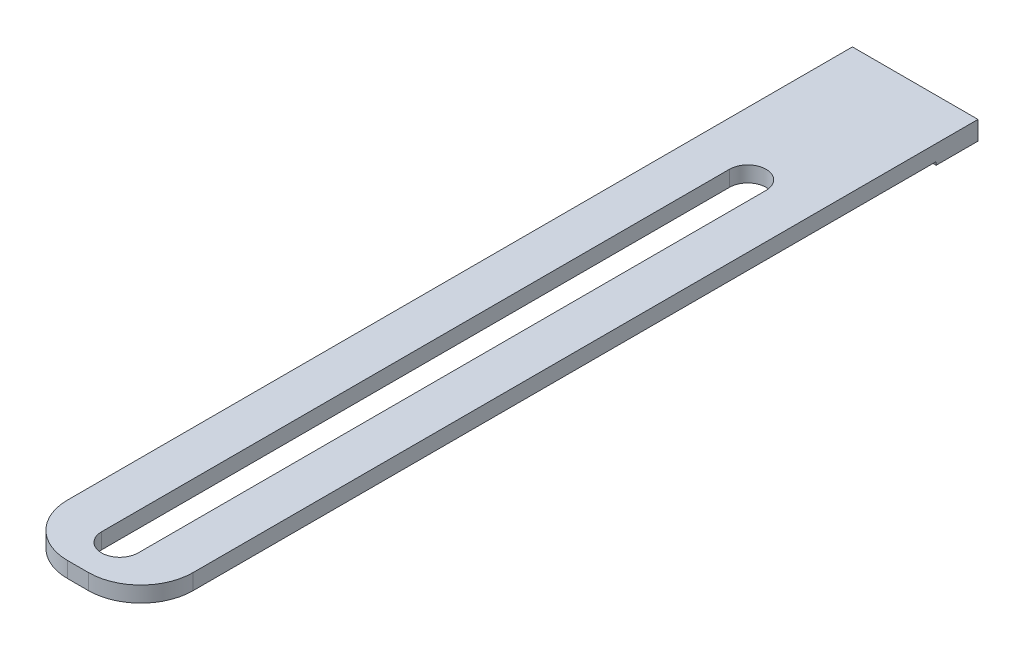
SolidWorks part; units mm, degrees
ref_plane "前视基准面" through (0, 0, 0) normal (0, 0, 1) x (1, 0, 0)
ref_plane "上视基准面" through (0, 0, 0) normal (0, 1, 0) x (1, 0, 0)
ref_plane "右视基准面" through (0, 0, 0) normal (1, 0, 0) x (0, 0, -1)
other "Configuration Table"
sketch "草图1" plane through (0, 0, 0) normal (0, 1, 0) x (1, 0, 0)
  line L0 (0, -36) -> (0, 24) construction
  line L1 (-6, 40) -> (6, 40)
  line L2 (-6, 40) -> (-6, -35)
  line L3 (-1, -40) -> (1, -40)
  line L4 (6, 40) -> (6, -35)
  line L5 (-6, 40) -> (6, -40) construction
  line L6 (-6, -40) -> (6, 40) construction
  line L7 (-1.75, -36) -> (-1.75, 24)
  line L8 (1.75, -36) -> (1.75, 24)
  arc A0 (-1.75, -36) -> (1.75, -36) centre (0, -36) ccw
  arc A1 (1.75, 24) -> (-1.75, 24) centre (0, 24) ccw
  arc A2 (1, -40) -> (6, -35) centre (1, -35) ccw
  arc A3 (-6, -35) -> (-1, -40) centre (-1, -35) ccw
  point P0 (0, 0)
  point P8 (0, -6)
  dimension "D4" = 4
  dimension "D6" = 5
  dimension "D1" = 12
  dimension "D2" = 80
  dimension "D3" = 60
  dimension "D5" = 3.5
extrude "凸台-拉伸1" add sketch "草图1" along normal blind 1.5
sketch "草图2" plane through (0, 0, 0) normal (0, -1, 0) x (1, 0, 0)
  line L0 (-6, -40) -> (-6, 35) construction
  line L1 (6, -40) -> (-6, -40)
  line L2 (6, -40) -> (6, -36)
  line L3 (6, -36) -> (-6, -36)
  line L4 (-6, -40) -> (-6, -36)
  dimension "D1" = 4
extrude "凸台-拉伸2" add sketch "草图2" along normal blind 0.3
